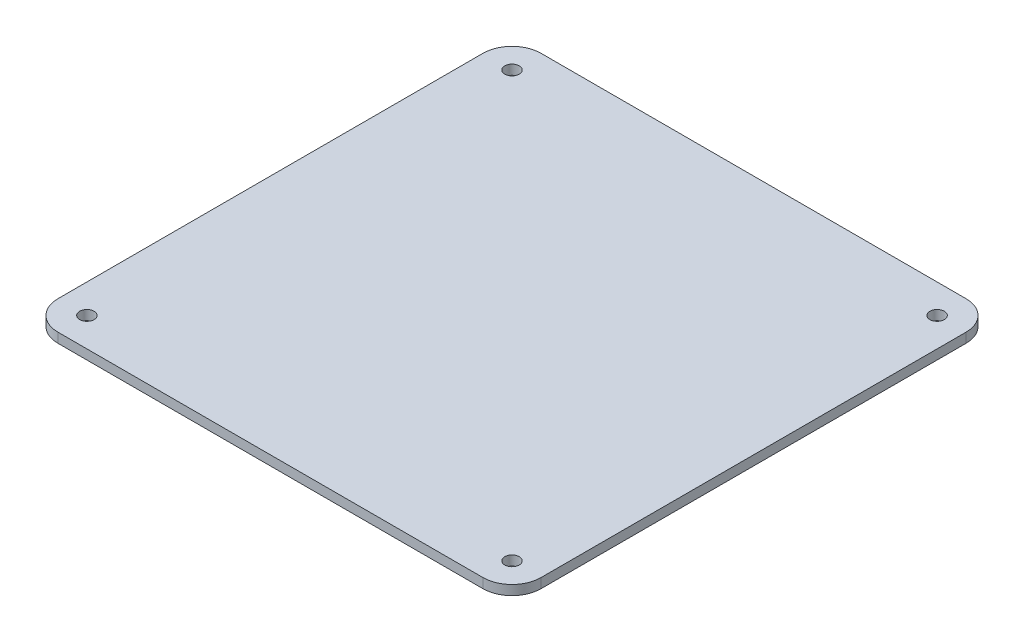
SolidWorks part; units mm, degrees
ref_plane "Front Plane" through (0, 0, 0) normal (0, 0, 1) x (1, 0, 0)
ref_plane "Top Plane" through (0, 0, 0) normal (0, 1, 0) x (1, 0, 0)
ref_plane "Right Plane" through (0, 0, 0) normal (1, 0, 0) x (0, 0, -1)
sketch "Sketch1" plane through (0, 0, 0) normal (0, 1, 0) x (1, 0, 0)
  line L1 (50, 50) -> (-50, 50)
  line L2 (50, 50) -> (50, -50)
  line L3 (50, -50) -> (-50, -50)
  line L4 (-50, 50) -> (-50, -50)
  line L5 (50, 50) -> (-50, -50) construction
  line L6 (50, -50) -> (-50, 50) construction
  point P0 (0, 0)
  dimension "D1" = 100
  dimension "D2" = 100
extrude "Boss-Extrude1" add sketch "Sketch1" along normal blind 2
fillet "Fillet1" radius 6 4 edges at (-50, 1, 50) (50, 1, 50) (50, 1, -50) (-50, 1, -50)
sketch "Sketch2" plane through (0, 2, 0) normal (0, 1, 0) x (1, 0, 0)
  line L0 (-44, -44) -> (-48.2426, -48.2426) construction
  arc A0 (-50, -44) -> (-44, -50) centre (-44, -44) ccw construction
  circle A1 centre (-44, -44) radius 1.5
  circle A2 centre (-44, 44) radius 1.5
  circle A3 centre (44, 44) radius 1.5
  circle A4 centre (44, -44) radius 1.5
  point P16 (0, 0)
  dimension "D1" = 3
  dimension "D2" = 4
extrude "Cut-Extrude1" cut sketch "Sketch2" against normal through all
